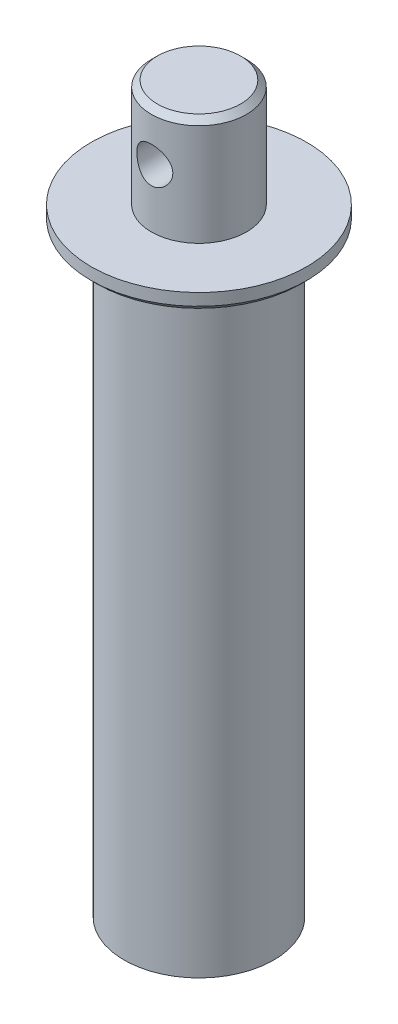
SolidWorks part; units mm, degrees
material "普通碳钢"
ref_plane "前视基准面" through (0, 0, 0) normal (0, 0, 1) x (1, 0, 0)
ref_plane "上视基准面" through (0, 0, 0) normal (0, 1, 0) x (1, 0, 0)
ref_plane "右视基准面" through (0, 0, 0) normal (1, 0, 0) x (0, 0, -1)
sketch "草图1" plane through (0, 0, 0) normal (0, 1, 0) x (1, 0, 0)
  circle A0 centre (0, 0) radius 7.95
  dimension "D1" = 15.9
extrude "凸台-拉伸1" add sketch "草图1" along normal blind 18 contours A0
chamfer "倒角2" distance 1 angle 45 1 edges at (0, 18, 7.95)
sketch "草图4" plane through (0, 0, 0) normal (0, 1, 0) x (1, 0, 0)
  circle A0 centre (0, 0) radius 18
extrude "凸台-拉伸2" add sketch "草图4" against normal blind 3
chamfer "倒角1" distance 1 angle 45 1 edges at (0, -3, 18)
ref_plane "基准面4" through (0, -3, 0) normal (0, -1, 0) x (-1, 0, 0)
sketch "草图5" plane through (0, -3, 0) normal (0, -1, 0) x (-1, 0, 0)
  circle A0 centre (0, 0) radius 12.5
extrude "凸台-拉伸3" add sketch "草图5" along normal blind 100
ref_plane "基准面5" through (0, -103, 0) normal (0, -1, 0) x (-1, 0, 0)
sketch "草图9" plane through (0, 0, 0) normal (0, 0, 1) x (1, 0, 0)
  line L0 (0, -19.8) -> (0, 19.8) construction
  line L1 (19.8, 0) -> (-19.8, 0) construction
  circle A0 centre (0, 9.7) radius 3
  dimension "D1" = 9.7
  dimension "D2" = 6
extrude "切除-拉伸2" cut sketch "草图9" against normal through all both and the other way through all
sketch "草图10" plane through (0, -3, 0) normal (0, -1, 0) x (-1, 0, 0)
  circle A0 centre (0, 0) radius 7.95
extrude "切除-拉伸3" cut sketch "草图10" along normal up to surface (90 mm away) from offset 10 up to face at (0, -103, -12.5)
